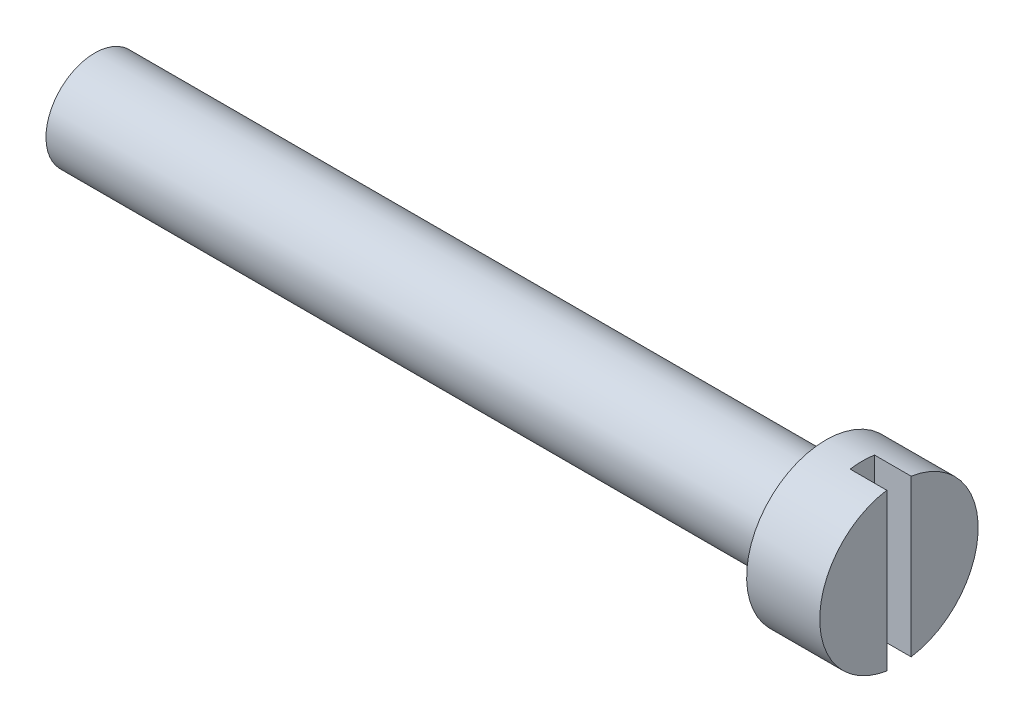
SolidWorks part; units mm, degrees
material "AISI 316 Stainless Steel Sheet (SS)"
ref_plane "Front Plane" through (0, 0, 0) normal (0, 0, 1) x (1, 0, 0)
ref_plane "Top Plane" through (0, 0, 0) normal (0, 1, 0) x (1, 0, 0)
ref_plane "Right Plane" through (0, 0, 0) normal (1, 0, 0) x (0, 0, -1)
sketch "Sketch1" plane through (0, 0, 0) normal (0, 0, 1) x (1, 0, 0)
  line L0 (0, 0) -> (-33, 0)
  line L1 (-33, 0) -> (-33, 2)
  line L2 (-33, 2) -> (-3, 2)
  line L3 (-3, 2) -> (-3, 3.25)
  line L4 (-3, 3.25) -> (0, 3.25)
  line L5 (0, 3.25) -> (0, 0)
  dimension "D1" = 3
  dimension "D2" = 30
  dimension "D3" = 2
  dimension "D4" = 3.25
revolve "Revolve1" add sketch "Sketch1" angle 360 about L0
sketch "Sketch2" plane through (0, 0, 0) normal (1, 0, 0) x (0, 0, -1)
  line L1 (-0.5, -3.25) -> (0.5, -3.25)
  line L2 (-0.5, -3.25) -> (-0.5, 3.25)
  line L3 (-0.5, 3.25) -> (0.5, 3.25)
  line L4 (0.5, -3.25) -> (0.5, 3.25)
  line L5 (-0.5, -3.25) -> (0.5, 3.25) construction
  line L6 (-0.5, 3.25) -> (0.5, -3.25) construction
  circle A0 centre (0, 0) radius 3.25 construction
  point P0 (0, 0)
  dimension "D1" = 1
extrude "Cut-Extrude1" cut sketch "Sketch2" against normal blind 1.5
